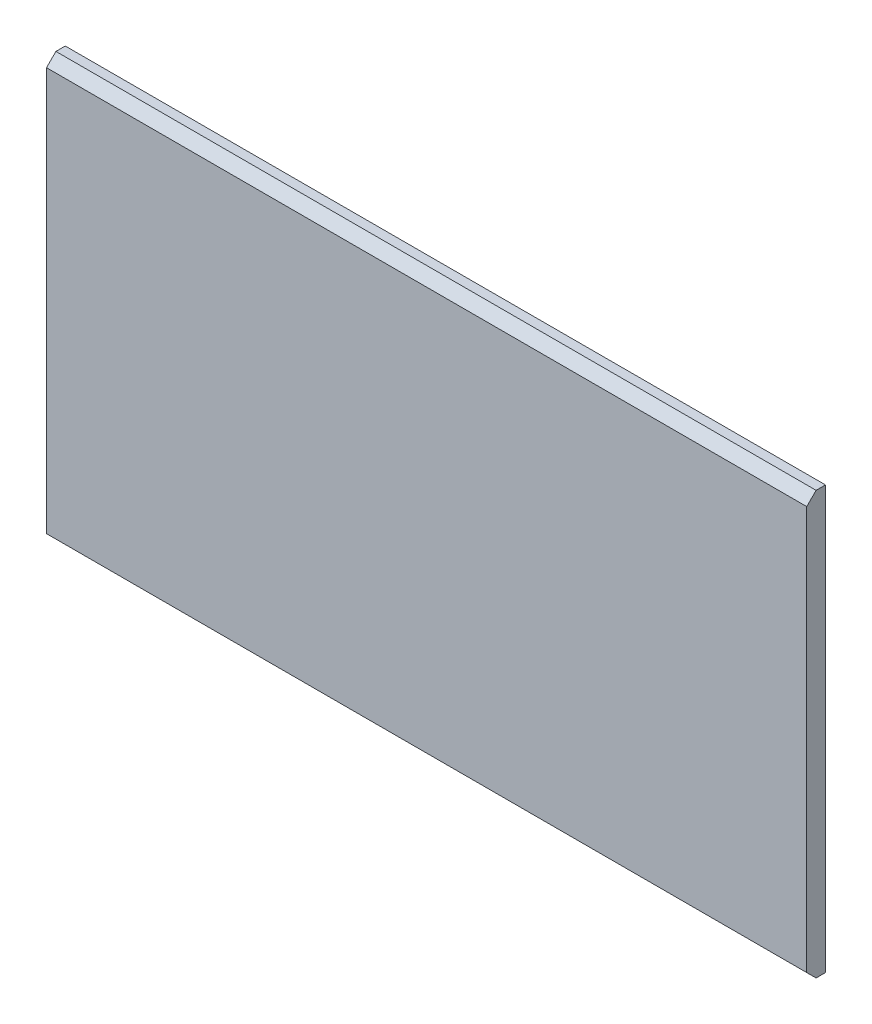
SolidWorks part; units mm, degrees
ref_plane "前视基准面" through (0, 0, 0) normal (0, 0, 1) x (1, 0, 0)
ref_plane "上视基准面" through (0, 0, 0) normal (0, 1, 0) x (1, 0, 0)
ref_plane "右视基准面" through (0, 0, 0) normal (1, 0, 0) x (0, 0, -1)
sketch "草图1" plane through (0, 0, 0) normal (0, 0, 1) x (1, 0, 0)
  line L1 (-202.5, 112.5) -> (202.5, 112.5)
  line L2 (-202.5, 112.5) -> (-202.5, -112.5)
  line L3 (-202.5, -112.5) -> (202.5, -112.5)
  line L4 (202.5, 112.5) -> (202.5, -112.5)
  line L5 (-202.5, 112.5) -> (202.5, -112.5) construction
  line L6 (-202.5, -112.5) -> (202.5, 112.5) construction
  point P0 (0, 0)
  dimension "D1" = 225
  dimension "D2" = 405
extrude "凸台-拉伸1" add sketch "草图1" along normal blind 10
chamfer "倒角1" distance 5 angle 45 2 edges at (0, -112.5, 10) (0, 112.5, 10)
